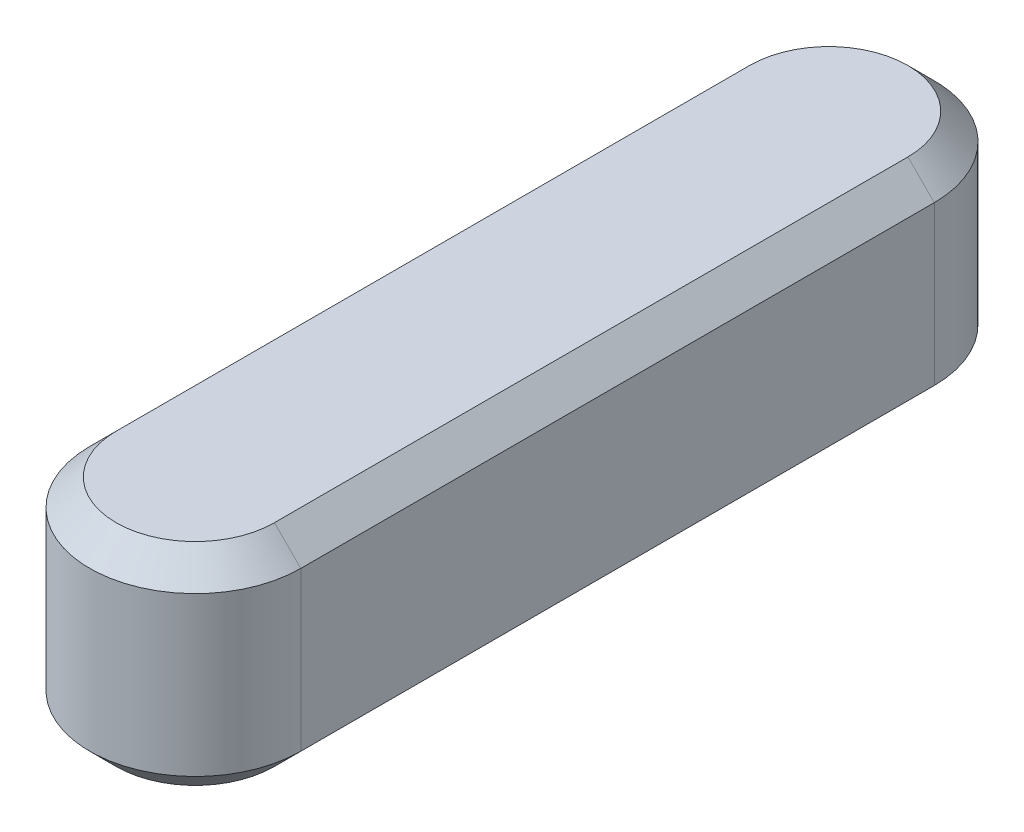
SolidWorks part; units mm, degrees
ref_plane "Přední rovina" through (0, 0, 0) normal (0, 0, 1) x (1, 0, 0)
ref_plane "Vrchní rovina" through (0, 0, 0) normal (0, 1, 0) x (1, 0, 0)
ref_plane "Pravá rovina" through (0, 0, 0) normal (1, 0, 0) x (0, 0, -1)
sketch "Skica1" plane through (0, 0, 0) normal (0, 1, 0) x (1, 0, 0)
  line L0 (-1, 3) -> (-1, -3)
  line L1 (1, -3) -> (1, 3)
  line L2 (0, 3) -> (0, -3) construction
  arc A0 (-1, -3) -> (1, -3) centre (0, -3) ccw
  arc A1 (1, 3) -> (-1, 3) centre (0, 3) ccw
  dimension "l" = 8
  dimension "b" = 2
extrude "Vysunout1" add sketch "Skica1" along normal mid plane 2
chamfer "Zkosit1" distance 0.25 angle 45 8 edges at (0, 1, 4) (1, 1, 0) (0, 1, -4) (1, -1, 0) (0, -1, 4) (-1, -1, 0) (0, -1, -4) (-1, 1, 0)
